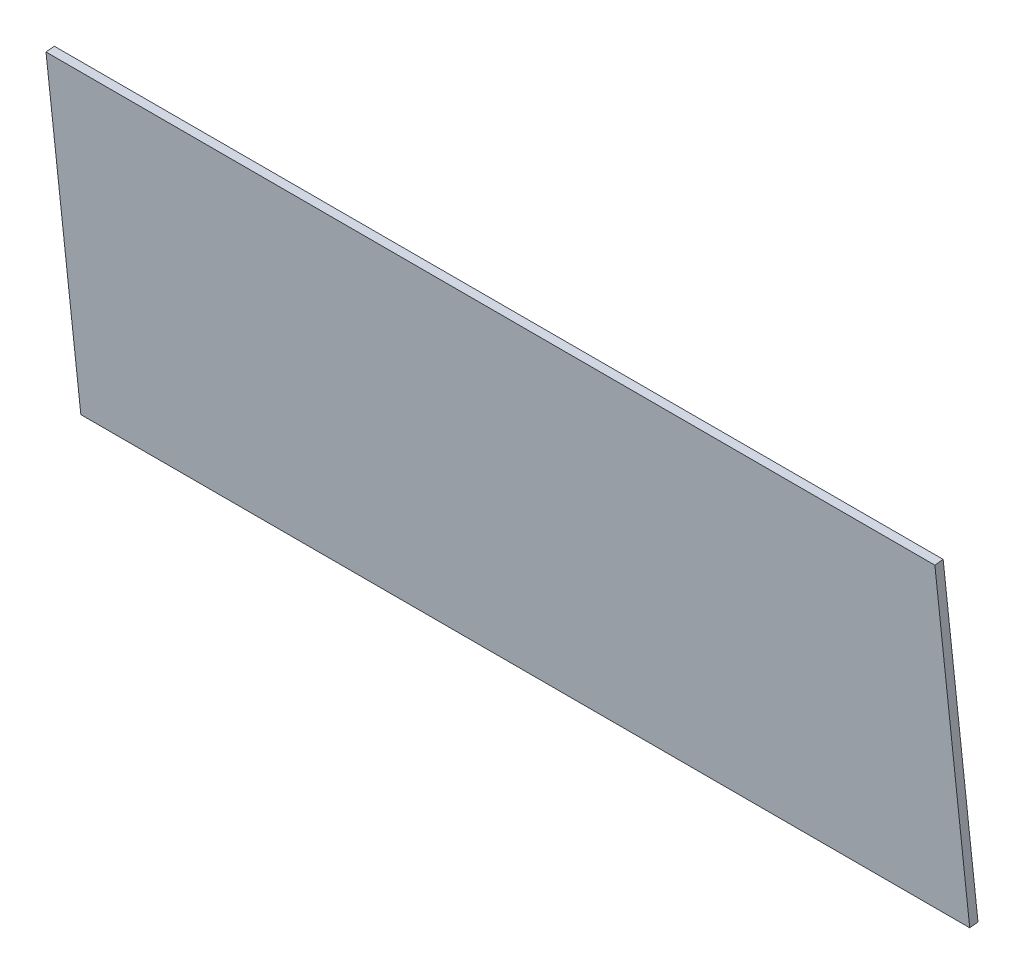
SolidWorks part; units mm, degrees
ref_plane "Front Plane" through (0, 0, 0) normal (0, 0, 1) x (1, 0, 0)
ref_plane "Top Plane" through (0, 0, 0) normal (0, 1, 0) x (1, 0, 0)
ref_plane "Right Plane" through (0, 0, 0) normal (1, 0, 0) x (0, 0, -1)
sketch "Sketch1" plane through (0, 21.8362, -207.7576) normal (0, -0.1045, 0.9945) x (0.9644, -0.2632, -0.0277)
  line L1 (206.1943, -1065.3037) -> (514.7886, -980.6307)
  line L2 (206.1943, -1065.3037) -> (237.9467, -1181.0265)
  line L3 (237.9467, -1181.0265) -> (546.541, -1096.3535)
  line L4 (514.7886, -980.6307) -> (546.541, -1096.3535)
  line L5 (206.1943, -1065.3037) -> (546.541, -1096.3535) construction
  line L6 (237.9467, -1181.0265) -> (514.7886, -980.6307) construction
  point P4 (376.3677, -1080.8286)
  point P7 (0, 0)
  point P9 (0, 0)
  point P10 (229.782, -1171.7212)
  point P11 (216.261, -1176.8712)
  point P16 (0, 0)
extrude "Boss-Extrude1" add sketch "Sketch1" along normal blind 3
